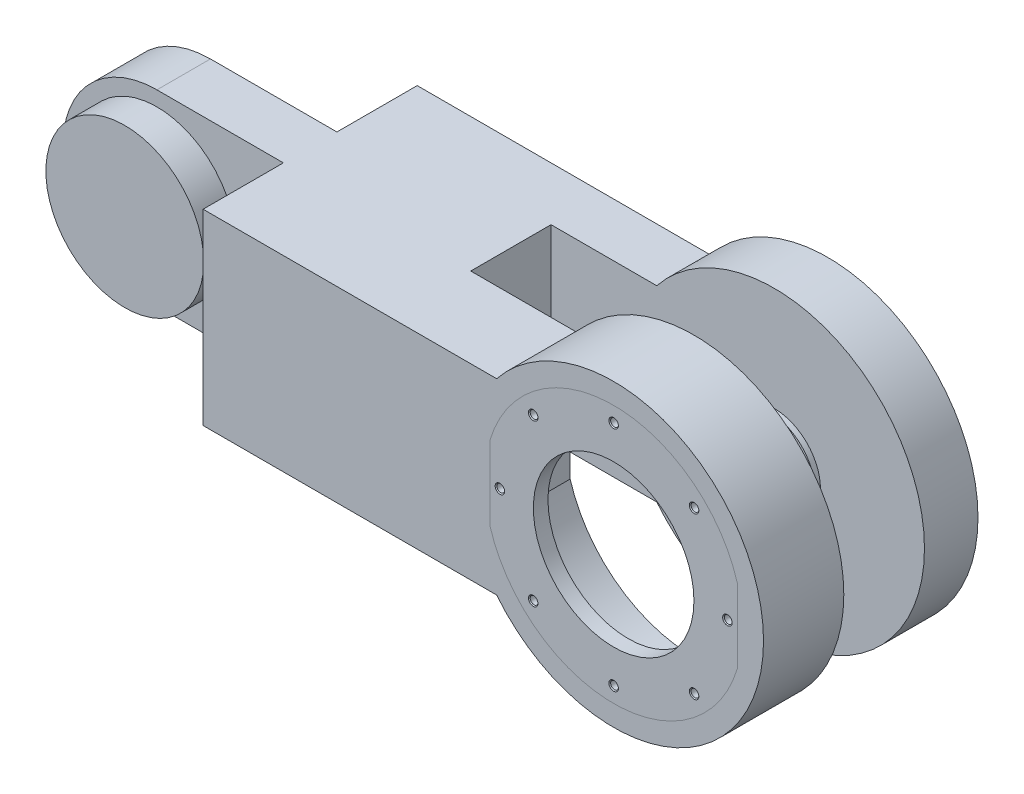
SolidWorks part; units mm, degrees
ref_plane "前视基准面" through (0, 0, 0) normal (0, 0, 1) x (1, 0, 0)
ref_plane "上视基准面" through (0, 0, 0) normal (0, 1, 0) x (1, 0, 0)
ref_plane "右视基准面" through (0, 0, 0) normal (1, 0, 0) x (0, 0, -1)
sketch "草图1" plane through (0, 0, 0) normal (0, 0, 1) x (1, 0, 0)
  line L0 (-50.7515, 21.0787) -> (49.2485, 21.0787)
  line L1 (-50.7515, -48.9213) -> (49.2485, -48.9213)
  line L2 (-50.7515, 21.0787) -> (-50.7515, -48.9213)
  line L3 (49.2485, 21.0787) -> (49.2485, -48.9213)
  dimension "D1" = 100
  dimension "D2" = 70
extrude "凸台-拉伸1" add sketch "草图1" along normal mid plane 80 contours L3 L1 L2 L0
sketch "草图2" plane through (0, 0, 0) normal (0, 0, 1) x (1, 0, 0)
  line L0 (-50.7515, 21.0787) -> (-88.0045, 21.0787)
  line L1 (-50.7515, -48.9213) -> (-88.0045, -48.9213)
  line L2 (-50.7515, -48.9213) -> (49.2485, -48.9213) construction
  line L3 (-50.7515, 21.0787) -> (-50.7515, -48.9213) construction
  line L4 (-50.7515, 21.0787) -> (-50.7515, -48.9213)
  arc A0 (-88.0045, 21.0787) -> (-88.0045, -48.9213) centre (-88.0045, -13.9213) ccw
  circle A1 centre (-88.0045, -13.9213) radius 32
extrude "凸台-拉伸2" add sketch "草图2" along normal mid plane 20
sketch "草图6" plane through (0, 0, 10) normal (0, 0, 1) x (1, 0, 0)
  circle A0 centre (-88.0045, -13.9213) radius 32
extrude "凸台-拉伸3" add sketch "草图6" against normal blind 8
sketch "草图7" plane through (0, 0, -40) normal (0, 0, -1) x (-1, 0, 0)
  line L0 (50.7515, 21.0787) -> (40.7515, 21.0787)
  line L1 (50.7515, 21.0787) -> (-49.2485, 21.0787) construction
  line L2 (40.7515, 21.0787) -> (40.7515, -48.9213)
  line L3 (50.7515, -48.9213) -> (-49.2485, -48.9213) construction
  line L4 (40.7515, -48.9213) -> (50.7515, -48.9213)
  line L5 (50.7515, -48.9213) -> (50.7515, 21.0787)
  dimension "D1" = 10
extrude "切除-拉伸1" cut sketch "草图7" against normal blind 30 contours L5 L0 L2 L4
sketch "草图9" plane through (0, 0, 40) normal (0, 0, 1) x (1, 0, 0)
  line L0 (-50.7515, 21.0787) -> (-40.7515, 21.0787)
  line L1 (-50.7515, 21.0787) -> (49.2485, 21.0787) construction
  line L2 (-40.7515, 21.0787) -> (-40.7515, -48.9213)
  line L3 (-40.7515, -48.9213) -> (-50.7515, -48.9213)
  line L4 (-50.7515, -48.9213) -> (-50.7515, 21.0787)
extrude "切除-拉伸2" cut sketch "草图9" against normal blind 30
sketch "草图10" plane through (0, 0, 40) normal (0, 0, 1) x (1, 0, 0)
  line L0 (49.2485, 21.0787) -> (69.2485, 21.0787)
  line L1 (49.2485, -48.9213) -> (69.2485, -48.9213)
  line L3 (66.3946, -0.1736) -> (66.3946, -27.669)
  line L4 (158.8946, -0.1736) -> (158.8946, -27.669)
  arc A0 (66.3946, -0.1736) -> (158.8946, -0.1736) centre (112.6446, -13.9213) cw
  arc A1 (158.8946, -27.669) -> (66.3946, -27.669) centre (112.6446, -13.9213) cw
  circle A2 centre (112.6446, -13.9213) radius 56
  dimension "D1" = 20
sketch "草图11" plane through (0, 0, 10) normal (0, 0, 1) x (1, 0, 0)
  circle A0 centre (-88.0045, -13.9213) radius 29.5
  dimension "D1" = 59
extrude "凸台-拉伸4" add sketch "草图11" along normal blind 12
extrude "凸台-拉伸5" add sketch "草图10" against normal blind 30
sketch "草图12" plane through (0, 0, 40) normal (0, 0, 1) x (1, 0, 0)
  line L0 (66.3946, -0.1736) -> (66.3946, -27.669)
  line L1 (158.8946, -0.1736) -> (158.8946, -27.669)
  arc A0 (66.3946, -0.1736) -> (158.8946, -0.1736) centre (112.6446, -13.9213) cw
  arc A1 (66.3946, -27.669) -> (158.8946, -27.669) centre (112.6446, -13.9213) ccw
extrude "凸台-拉伸6" add sketch "草图12" against normal blind 5.45 separate body
sketch "草图13" plane through (0, 0, 40) normal (0, 0, 1) x (1, 0, 0)
  circle A0 centre (112.6446, -13.9213) radius 30
extrude "切除-拉伸4" cut sketch "草图13" against normal blind 6
sketch "草图14" plane through (0, 0, 40) normal (0, 0, 1) x (1, 0, 0)
  circle A0 centre (112.6446, -13.9213) radius 42.5
  point P4 (112.6446, 28.5787)
hole_wizard "M3.5 螺纹孔3" positions "草图14" profile "草图15" tap size "M3.5" standard "GB"
sketch "草图15" plane through (112.6446, 28.5787, 40) normal (1, 0, 0) x (0, -1, 0)
  line L0 (0, 0) -> (0, 23.8712)
  line L1 (0, 23.8712) -> (1.45, 23)
  line L2 (1.45, 23) -> (1.45, 0.325)
  line L3 (1.45, 0.325) -> (1.775, 0)
  line L5 (1.775, 0) -> (0, 0)
  line L6 (-1.45, 0.325) -> (-1.775, 0) construction
  line L10 (0, 23.8712) -> (-1.45, 23) construction
  line L11 (0, -6.35) -> (0, 107.95) construction
  dimension "螺纹孔钻头直径" = 2.9
  dimension "螺纹孔钻头深度" = 23
  dimension "近端锥形沉头孔直径" = 3.55
  dimension "近端锥形沉头孔角度" = 90
  dimension "导头角度" = 118
pattern_circular "阵列(圆周)1" count 8 every 45 about axis through (112.6446, -13.9213, 0) along (0, 0, 1) of "M3.5 螺纹孔3"
sketch "草图16" plane through (0, 0, 2) normal (0, 0, -1) x (-1, 0, 0)
  circle A0 centre (88.0045, -13.9213) radius 17.25
  point P4 (70.7545, -13.9213)
hole_wizard "M4 螺纹孔1" positions "草图16" profile "草图17" tap size "M4" standard "GB"
sketch "草图17" plane through (-70.7545, -13.9213, 2) normal (1, 0, 0) x (0, 1, 0)
  line L0 (0, 0) -> (0, 12.4914)
  line L1 (0, 12.4914) -> (1.65, 11.5)
  line L2 (1.65, 11.5) -> (1.65, 0.375)
  line L3 (1.65, 0.375) -> (2.025, 0)
  line L5 (2.025, 0) -> (0, 0)
  line L6 (-1.65, 0.375) -> (-2.025, 0) construction
  line L10 (0, 12.4914) -> (-1.65, 11.5) construction
  line L11 (0, -6.35) -> (0, 107.95) construction
  dimension "螺纹孔钻头直径" = 3.3
  dimension "螺纹孔钻头深度" = 11.5
  dimension "近端锥形沉头孔直径" = 4.05
  dimension "近端锥形沉头孔角度" = 90
  dimension "导头角度" = 118
pattern_circular "阵列(圆周)2" count 6 every 60 about axis through (-88.0045, -13.9213, 0) along (0, 0, 1) of "M4 螺纹孔1"
sketch "草图18" plane through (0, 0, -40) normal (0, 0, -1) x (-1, 0, 0)
  line L0 (-49.2485, 21.0787) -> (-68.9296, 21.0787)
  line L1 (-49.2485, -48.9213) -> (-68.9296, -48.9213)
  line L2 (-68.9296, 21.0787) -> (-49.2485, 21.0787)
  line L3 (-68.9296, -48.9213) -> (-49.2485, -48.9213)
  circle A0 centre (-112.6446, -13.9213) radius 56.136
extrude "凸台-拉伸7" add sketch "草图18" against normal blind 20
sketch "草图19" plane through (0, 0, -20) normal (0, 0, 1) x (1, 0, 0)
  circle A0 centre (112.6446, -13.9213) radius 17.25
extrude "凸台-拉伸8" add sketch "草图19" along normal blind 2
sketch "草图22" plane through (49.2485, 0, 0) normal (1, 0, 0) x (0, 0, -1)
  line L0 (20, 21.0787) -> (20, -48.9213)
  line L1 (20, 21.0787) -> (-10, 21.0787)
  line L2 (-10, 21.0787) -> (-10, -48.9213)
  line L3 (-10, -48.9213) -> (20, -48.9213)
extrude "切除-拉伸6" cut sketch "草图22" against normal blind 20
